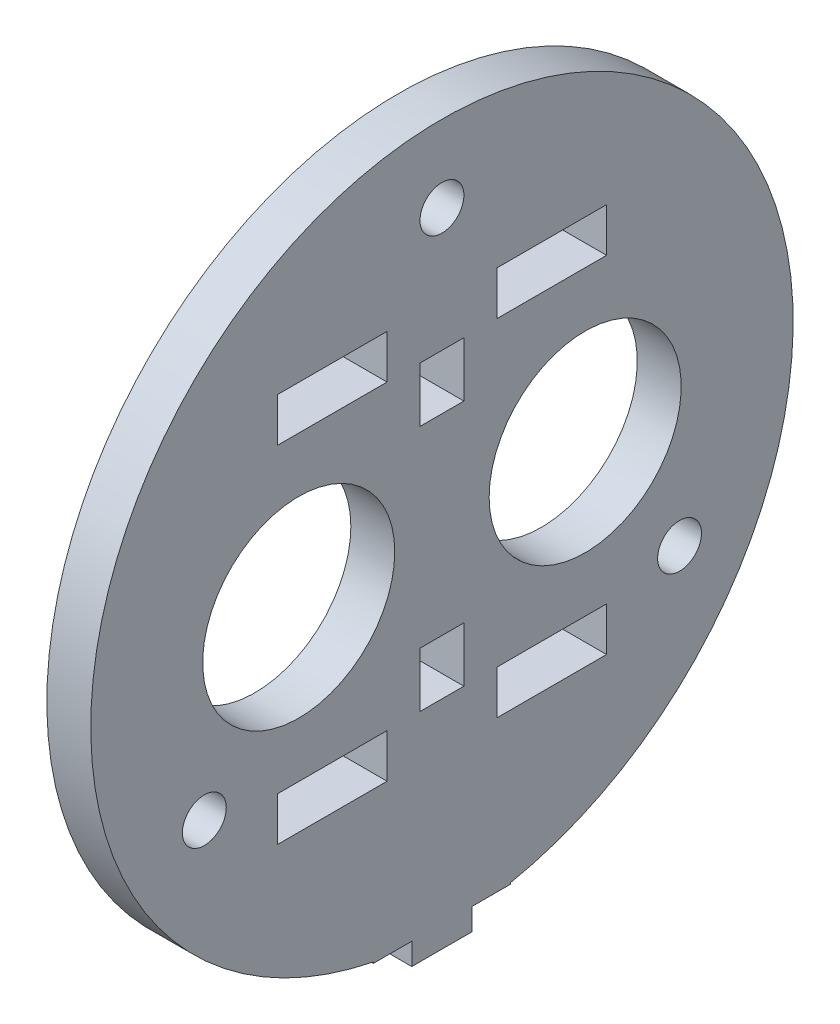
SolidWorks part; units mm, degrees
ref_plane "Front Plane" through (0, 0, 0) normal (0, 0, 1) x (1, 0, 0)
ref_plane "Top Plane" through (0, 0, 0) normal (0, 1, 0) x (1, 0, 0)
ref_plane "Right Plane" through (0, 0, 0) normal (1, 0, 0) x (0, 0, -1)
sketch "Sketch1" plane through (0, 0, 0) normal (1, 0, 0) x (0, 0, -1)
  line L0 (0, 86.3618) -> (0, -95.6447) construction
  line L1 (-89.4162, 0) -> (80.9544, 0) construction
  line L5 (-12.5, -62.7674) -> (-12.5, -67)
  line L6 (-12.5, -67) -> (12.5, -67)
  line L7 (12.5, -62.7674) -> (12.5, -67)
  circle A0 centre (0, 0) radius 75 construction
  circle A1 centre (0, 50) radius 4
  circle A2 centre (43.3013, -25) radius 4
  circle A3 centre (-43.3013, -25) radius 4
  circle A4 centre (-26.1, 0) radius 17.5
  circle A5 centre (26.1, 0) radius 17.5
  arc A6 (12.5, -62.7674) -> (-12.5, -62.7674) centre (0, 0) ccw
  circle A7 centre (-26.1, 0) radius 22.1 construction
  point P14 (0, 0)
  point P16 (0, -75)
  point P20 (-4, 0)
  point P27 (0, -67)
  point P30 (0, 56.7762)
  point P31 (0, 56.7762)
  dimension "D1" = 150
  dimension "D2" = 8
  dimension "D5" = 35
  dimension "D9" = 8
  dimension "D7" = 64
  dimension "D10" = 44.2
  dimension "D3" = 50
  dimension "D6" = 8
  dimension "D8" = 25
  dimension "D4" = 3
extrude "Boss-Extrude1" add sketch "Sketch1" along normal blind 8
sketch "Sketch2" plane through (0, 0, 0) normal (-1, 0, 0) x (0, 0, 1)
  line L0 (0, -90.2636) -> (0, 91.611) construction
  line L1 (-93.4475, 0) -> (84.8595, 0) construction
  line L2 (10, -27.5) -> (10, -35.5)
  line L3 (-30, -27.5) -> (-10, -27.5)
  line L4 (-30, -27.5) -> (-30, -35.5)
  line L5 (-30, -35.5) -> (-10, -35.5)
  line L6 (-10, -27.5) -> (-10, -35.5)
  line L7 (30, -35.5) -> (10, -35.5)
  line L8 (30, -27.5) -> (30, -35.5)
  line L9 (30, -27.5) -> (10, -27.5)
  line L10 (30, 27.5) -> (10, 27.5)
  line L11 (30, 27.5) -> (30, 35.5)
  line L12 (30, 35.5) -> (10, 35.5)
  line L13 (-10, 27.5) -> (-10, 35.5)
  line L14 (-30, 35.5) -> (-10, 35.5)
  line L15 (-30, 27.5) -> (-30, 35.5)
  line L16 (-30, 27.5) -> (-10, 27.5)
  line L17 (10, 27.5) -> (10, 35.5)
  line L18 (4, 17.5) -> (4, 27.5)
  line L19 (-4, -17.5) -> (4, -17.5)
  line L20 (-4, -17.5) -> (-4, -27.5)
  line L21 (-4, -27.5) -> (4, -27.5)
  line L22 (4, -17.5) -> (4, -27.5)
  line L23 (-4, 27.5) -> (4, 27.5)
  line L24 (-4, 17.5) -> (-4, 27.5)
  line L25 (-4, 17.5) -> (4, 17.5)
  line L26 (5.5, -67) -> (5.5, -63)
  line L27 (-12.5, -67) -> (-5.5, -67)
  line L28 (-12.5, -67) -> (-12.5, -63)
  line L29 (-12.5, -63) -> (-5.5, -63)
  line L30 (-5.5, -67) -> (-5.5, -63)
  line L31 (12.5, -63) -> (5.5, -63)
  line L32 (12.5, -67) -> (12.5, -63)
  line L33 (12.5, -67) -> (5.5, -67)
  point P26 (0, -17.5)
  dimension "D1" = 27.5
  dimension "D2" = 20
  dimension "D3" = 20
  dimension "D4" = 8
  dimension "D5" = 8
  dimension "D6" = 10
  dimension "D7" = 4
  dimension "D8" = 7
extrude "Cut-Extrude1" cut sketch "Sketch2" against normal up to next
